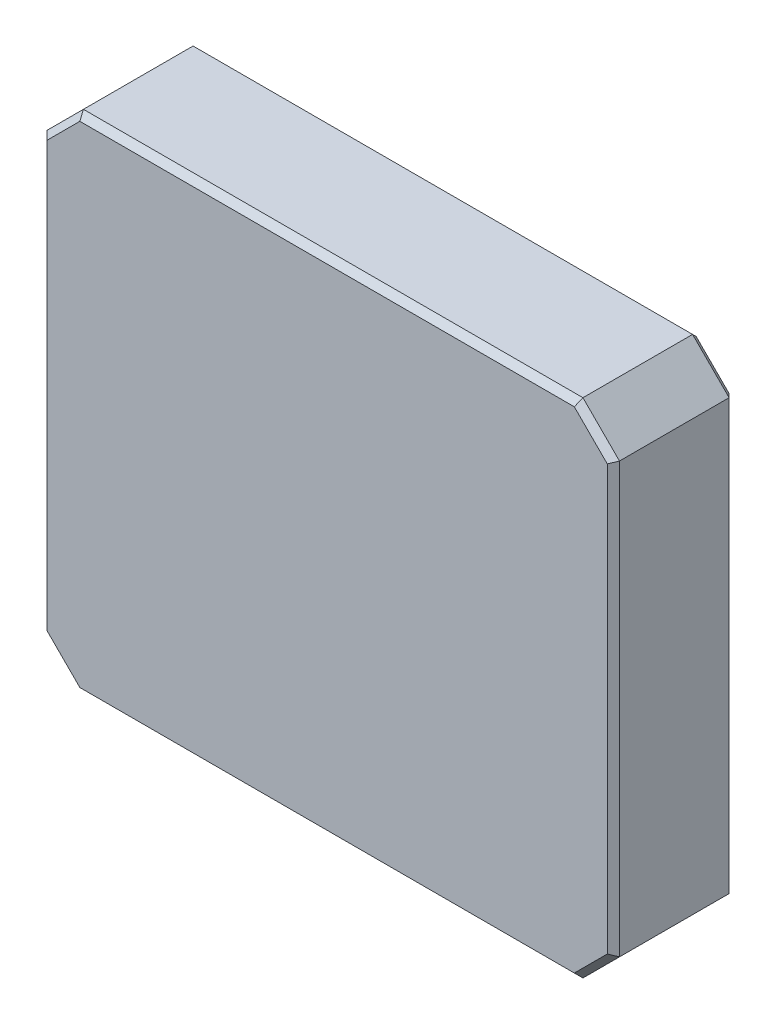
SolidWorks part; units mm, degrees
ref_plane "Front Plane" through (0, 0, 0) normal (0, 0, 1) x (1, 0, 0)
ref_plane "Top Plane" through (0, 0, 0) normal (0, 1, 0) x (1, 0, 0)
ref_plane "Right Plane" through (0, 0, 0) normal (1, 0, 0) x (0, 0, -1)
sketch "Sketch1" plane through (0, 0, 0) normal (0, 0, 1) x (1, 0, 0)
  line L0 (-47, 35.25) -> (-41, 41.25)
  line L1 (-41, -41.25) -> (41, -41.25)
  line L2 (-47, -35.25) -> (-47, 35.25)
  line L3 (-41, 41.25) -> (41, 41.25)
  line L4 (47, -35.25) -> (47, 35.25)
  line L5 (-47, -41.25) -> (47, 41.25) construction
  line L6 (-47, 41.25) -> (47, -41.25) construction
  line L7 (41, 41.25) -> (47, 35.25)
  line L8 (41, -41.25) -> (47, -35.25)
  line L9 (-47, -35.25) -> (-41, -41.25)
  point P0 (0, 0)
  dimension "D1" = 94
  dimension "D2" = 82.5
extrude "Boss-Extrude1" add sketch "Sketch1" along normal blind 20
chamfer "Chamfer1" distance 1 16 edges at (-44, 38.25, 20) (0, 41.25, 20) (44, 38.25, 20) (47, 0, 20) (44, -38.25, 20) (0, -41.25, 20) (-44, -38.25, 20) (-47, 0, 20) (-44, 38.25, 0) (0, 41.25, 0) (44, 38.25, 0) (47, 0, 0) (44, -38.25, 0) (0, -41.25, 0) (-44, -38.25, 0) (-47, 0, 0)
